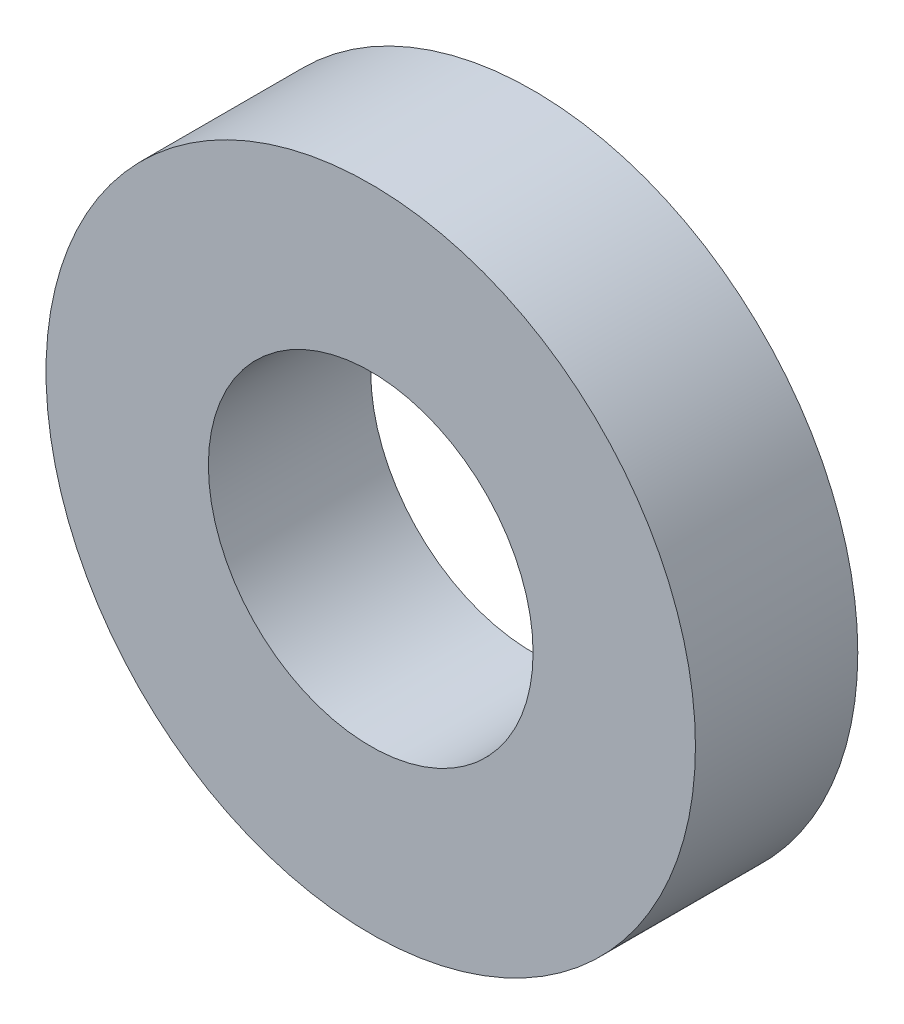
SolidWorks part; units mm, degrees
ref_plane "前视基准面" through (0, 0, 0) normal (0, 0, 1) x (1, 0, 0)
ref_plane "上视基准面" through (0, 0, 0) normal (0, 1, 0) x (1, 0, 0)
ref_plane "右视基准面" through (0, 0, 0) normal (1, 0, 0) x (0, 0, -1)
other "Configuration Table"
sketch "草图1" plane through (0, 0, 0) normal (0, 0, 1) x (1, 0, 0)
  circle A0 centre (0, 0) radius 15
  circle A1 centre (0, 0) radius 30
  dimension "D1" = 30
  dimension "D2" = 60
extrude "凸台-拉伸1" add sketch "草图1" along normal blind 15
